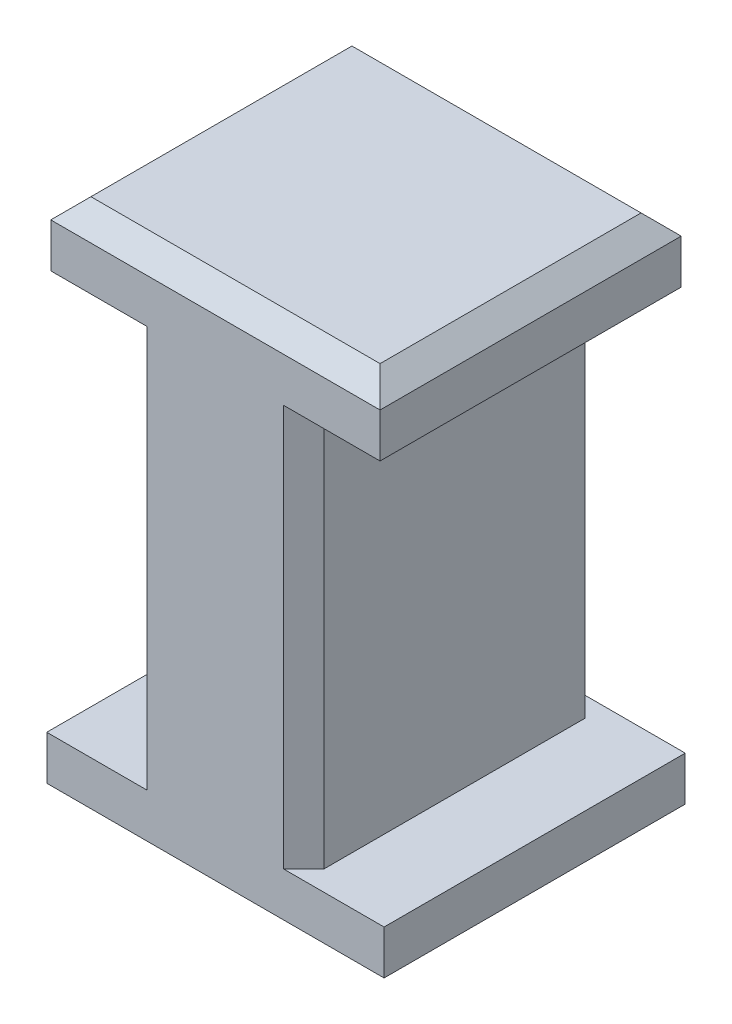
SolidWorks part; units mm, degrees
ref_plane "정면" through (0, 0, 0) normal (0, 0, 1) x (1, 0, 0)
ref_plane "윗면" through (0, 0, 0) normal (0, 1, 0) x (1, 0, 0)
ref_plane "우측면" through (0, 0, 0) normal (1, 0, 0) x (0, 0, -1)
sketch "스케치1" plane through (0, 0, 0) normal (0, 0, 1) x (1, 0, 0)
  line L0 (0, 0) -> (0, 26.4) construction
  line L1 (-8.4, 0) -> (8.4, 0)
  line L2 (8.4, 0) -> (8.4, 3.2)
  line L3 (-8.4, 0) -> (-8.4, 3.2)
  line L4 (8.4, 3.2) -> (4.4, 3.2)
  line L5 (-8.4, 3.2) -> (-4.4, 3.2)
  line L6 (4.4, 3.2) -> (4.4, 23.2)
  line L7 (-4.4, 3.2) -> (-4.4, 23.2)
  line L8 (4.4, 23.2) -> (8.2, 23.2)
  line L9 (-4.4, 23.2) -> (-8.2, 23.2)
  line L10 (8.2, 23.2) -> (8.2, 26.4)
  line L11 (-8.2, 23.2) -> (-8.2, 26.4)
  line L12 (8.2, 26.4) -> (-8.2, 26.4)
  dimension "D1" = 3.2
  dimension "D2" = 16.8
  dimension "D3" = 20
  dimension "D4" = 26.4
  dimension "D5" = 3.8
  dimension "D6" = 8.8
extrude "보스-돌출1" add sketch "스케치1" along normal blind 15 contours L12 L11 L9 L7 L5 L3 L1 L2 L4 L6 L8 L10
chamfer "모따기1" distance 1 angle 45 12 edges at (8.2, 26.4, 7.5) (0, 26.4, 15) (-8.2, 26.4, 7.5) (0, 26.4, 0) (-4.4, 13.2, 15) (4.4, 13.2, 15) (-4.4, 13.2, 0) (4.4, 13.2, 0) (-8.4, 0, 7.5) (0, 0, 0) (8.4, 0, 7.5) (0, 0, 15)
